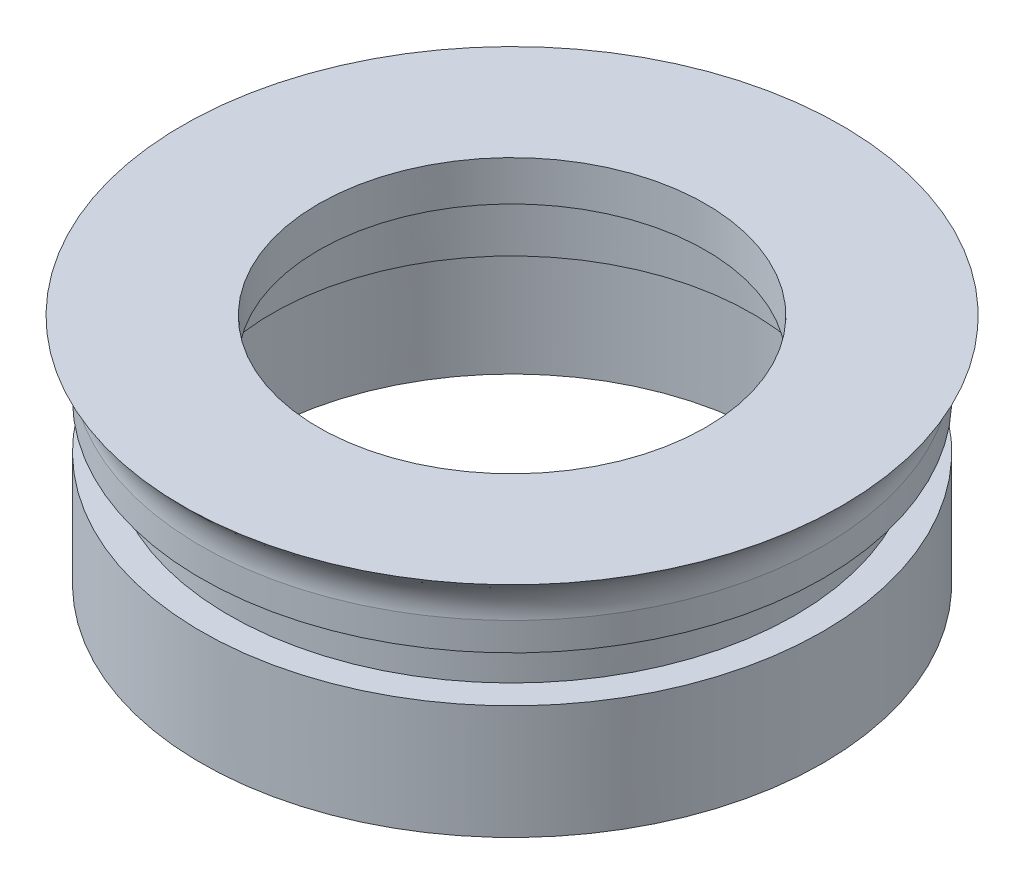
SolidWorks part; units mm, degrees
material "1023 Karbon Çeliği Levha (SS)"
ref_plane "Ön Düzlem" through (0, 0, 0) normal (0, 0, 1) x (1, 0, 0)
ref_plane "Üst Düzlem" through (0, 0, 0) normal (0, 1, 0) x (1, 0, 0)
ref_plane "Sağ Düzlem" through (0, 0, 0) normal (1, 0, 0) x (0, 0, -1)
sketch "Çizim1" plane through (0, 0, 0) normal (0, 0, 1) x (1, 0, 0)
  line L0 (0, 0) -> (0.0007, 14.087) construction
  line L1 (20.0046, 14.0864) -> (11.7523, 14.0864)
  line L2 (11.7523, 14.0864) -> (11.7523, 11.6505)
  line L3 (11.7523, 11.6505) -> (14.5567, 11.6505)
  line L4 (14.5567, 11.6505) -> (14.5567, 6.9331)
  line L5 (14.5567, 6.9331) -> (15.5719, 6.9331)
  line L6 (15.5719, 6.9331) -> (15.5848, -0.0008)
  line L7 (15.5848, -0.0008) -> (18.8692, -0.0008)
  line L8 (18.8692, -0.0008) -> (18.8692, 6.921)
  line L9 (18.8692, 6.921) -> (17.1728, 6.921)
  line L10 (17.1728, 6.921) -> (17.1728, 9.7028)
  line L11 (17.1728, 9.7028) -> (18.8692, 9.7028)
  line L12 (18.8692, 9.7028) -> (18.8692, 11.407)
  arc A0 (20.0046, 14.0864) -> (18.8692, 11.407) centre (21.8896, 11.7073) ccw
revolve "Döndür1" add sketch "Çizim1" angle 360 about L0
